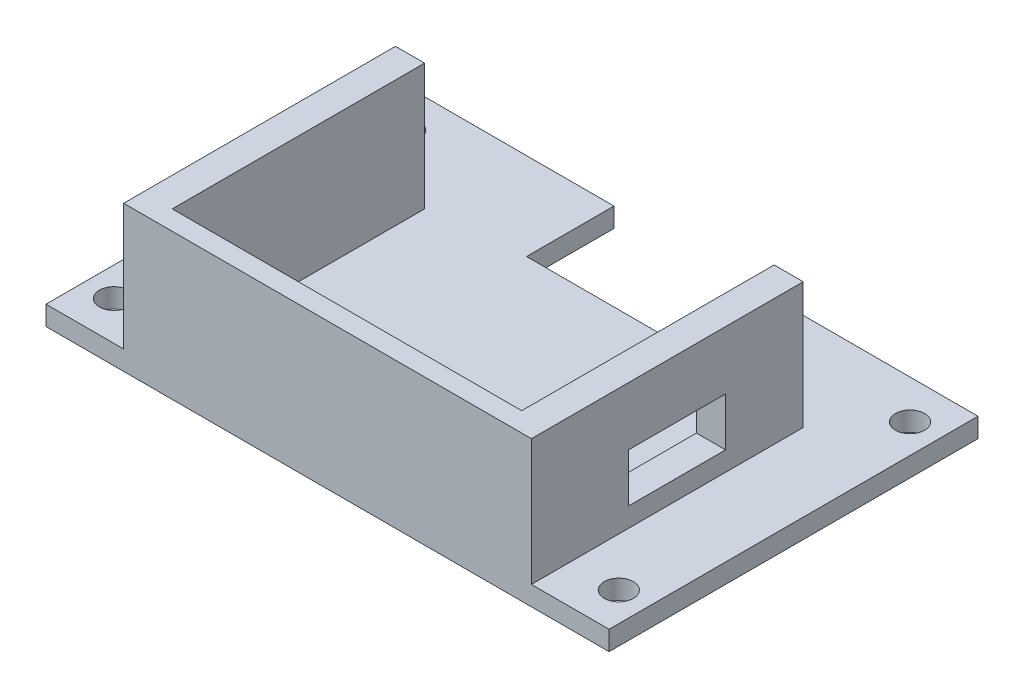
SolidWorks part; units mm, degrees
ref_plane "Front Plane" through (0, 0, 0) normal (0, 0, 1) x (1, 0, 0)
ref_plane "Top Plane" through (0, 0, 0) normal (0, 1, 0) x (1, 0, 0)
ref_plane "Right Plane" through (0, 0, 0) normal (1, 0, 0) x (0, 0, -1)
sketch "Sketch1" plane through (0, 0, 0) normal (0, 1, 0) x (1, 0, 0)
  line L1 (-29, -19) -> (29, -19)
  line L2 (-29, -19) -> (-29, 19)
  line L3 (-29, 19) -> (29, 19)
  line L4 (29, -19) -> (29, 19)
  line L5 (-29, -19) -> (29, 19) construction
  line L6 (-29, 19) -> (29, -19) construction
  point P0 (0, 0)
  dimension "D1" = 58
  dimension "D2" = 38
extrude "Boss-Extrude1" add sketch "Sketch1" along normal mid plane 2
sketch "Sketch2" plane through (0, 0, 0) normal (0, 1, 0) x (1, 0, 0)
  line L0 (29, 19) -> (-29, 19) construction
  line L1 (-8.5, 10) -> (8.5, 10)
  line L2 (-8.5, 10) -> (-8.5, 24.502)
  line L3 (-8.5, 24.502) -> (8.5, 24.502)
  line L4 (8.5, 10) -> (8.5, 24.502)
  line L5 (-8.5, 10) -> (8.5, 24.502) construction
  line L6 (-8.5, 24.502) -> (8.5, 10) construction
  point P0 (0, 17.251)
  dimension "D1" = 9
  dimension "D2" = 17
extrude "Cut-Extrude1" cut sketch "Sketch2" against normal through all both and the other way through all
sketch "Sketch3" plane through (0, 1, 0) normal (0, 1, 0) x (1, 0, 0)
  line L0 (0, 10) -> (0, -19) construction
  line L5 (-18, -18) -> (18, 9) construction
  line L6 (-18, 9) -> (18, -18) construction
  line L8 (-8.5, 10) -> (8.5, 10) construction
  line L9 (-29, -19) -> (29, -19) construction
  line L10 (18, 9) -> (21, 9)
  line L11 (18, 9) -> (18, -18)
  line L12 (18, -18) -> (21, -18)
  line L13 (21, 9) -> (21, -18)
  line L14 (-18, 9) -> (-21, 9)
  line L15 (-18, 9) -> (-18, -18)
  line L16 (-18, -18) -> (-21, -18)
  line L17 (-21, 9) -> (-21, -18)
  point P0 (0, -4.5)
  dimension "D1" = 36
  dimension "D2" = 27
  dimension "D3" = 3
  dimension "D4" = 18
  dimension "D5" = 18
  dimension "D6" = 18
extrude "Boss-Extrude2" add sketch "Sketch3" along normal blind 13
sketch "Sketch4" plane through (0, 1, 0) normal (0, 1, 0) x (1, 0, 0)
  line L1 (-21, -17) -> (21, -17)
  line L2 (-21, -17) -> (-21, -19)
  line L3 (-21, -19) -> (21, -19)
  line L4 (21, -17) -> (21, -19)
  line L6 (21, 9) -> (18, 9) construction
  line L7 (-29, -19) -> (29, -19) construction
  point P4 (0, -19)
  dimension "D1" = 26
  dimension "D2" = 0
  dimension "D3" = 42
extrude "Boss-Extrude3" add sketch "Sketch4" along normal blind 13
sketch "Sketch5" plane through (-21, 0, 0) normal (-1, 0, 0) x (0, 0, 1)
  line L0 (-19, 1) -> (19, 1) construction
  line L1 (-1, 3) -> (9, 3)
  line L2 (-1, 3) -> (-1, 8)
  line L3 (-1, 8) -> (9, 8)
  line L4 (9, 3) -> (9, 8)
  line L5 (-1, 3) -> (9, 8) construction
  line L6 (-1, 8) -> (9, 3) construction
  line L7 (-9, 14) -> (-9, 1) construction
  point P0 (4, 5.5)
  dimension "D1" = 10
  dimension "D2" = 5
  dimension "D3" = 2
  dimension "D4" = 8
extrude "Cut-Extrude2" cut sketch "Sketch5" against normal up to next from surface
sketch "Sketch6" plane through (0, 1, 0) normal (0, 1, 0) x (1, 0, 0)
  line L0 (-29, 19) -> (-29, -19) construction
  line L1 (0, 15.5397) -> (0, -27.8334) construction
  line L2 (-10.4545, 0) -> (10.848, 0) construction
  circle A0 centre (-26, 15) radius 1.5
  circle A1 centre (-26, -15) radius 1.5
  circle A2 centre (26, -15) radius 1.5
  circle A3 centre (26, 15) radius 1.5
  dimension "D1" = 3
  dimension "D2" = 3
  dimension "D3" = 15
extrude "Cut-Extrude3" cut sketch "Sketch6" against normal up to next
